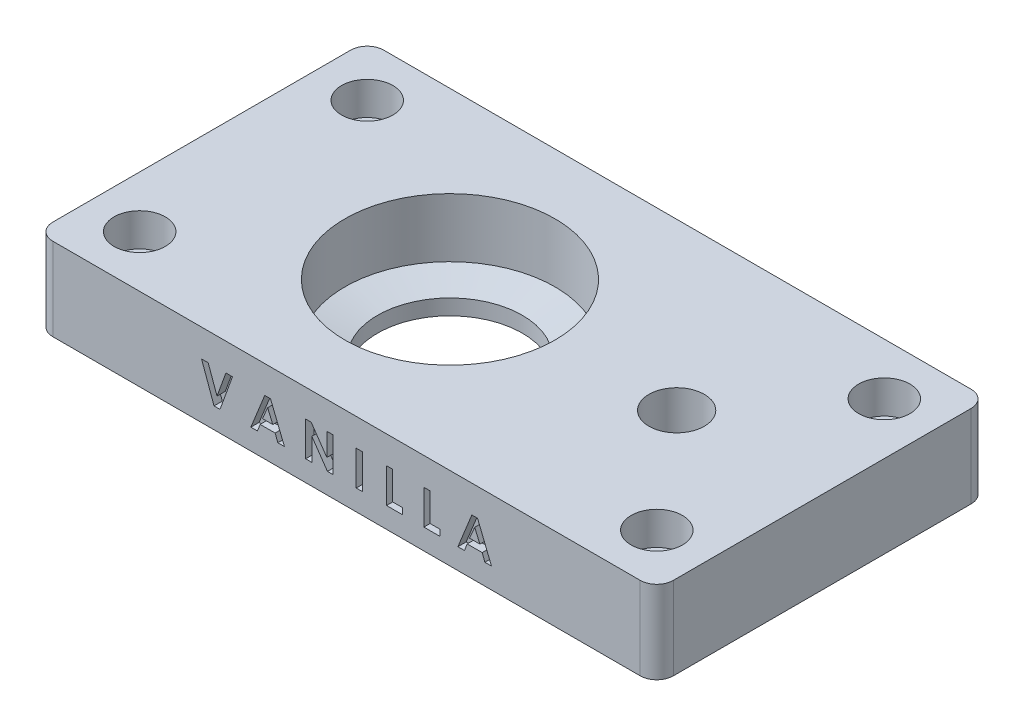
SolidWorks part; units mm, degrees
material "ABS"
ref_plane "Front Plane" through (0, 0, 0) normal (0, 0, 1) x (1, 0, 0)
ref_plane "Top Plane" through (0, 0, 0) normal (0, 1, 0) x (1, 0, 0)
ref_plane "Right Plane" through (0, 0, 0) normal (1, 0, 0) x (0, 0, -1)
sketch "Sketch1" plane through (0, 0, 0) normal (0, 1, 0) x (1, 0, 0)
  line L0 (0, 0) -> (34.798, 0) construction
  line L1 (-38.1, -25.4) -> (57.15, -25.4)
  line L2 (-38.1, -25.4) -> (-38.1, 25.4)
  line L3 (-38.1, 25.4) -> (57.15, 25.4)
  line L4 (57.15, -25.4) -> (57.15, 25.4)
  point P0 (0, 0)
  dimension "D1" = 95.25
  dimension "D2" = 50.8
  dimension "D3" = 34.798
extrude "Boss-Extrude1" add sketch "Sketch1" along normal blind 12.7
sketch "Sketch4" plane through (0, 12.7, 0) normal (0, 1, 0) x (1, 0, 0)
  line L5 (57.15, -25.4) -> (57.15, 25.4) construction
  line L6 (-38.1, -25.4) -> (57.15, -25.4) construction
  line L7 (57.15, 25.4) -> (-38.1, 25.4) construction
  line L8 (-38.1, 25.4) -> (-38.1, -25.4) construction
  circle A0 centre (-30.1625, 17.4625) radius 2.54
  circle A1 centre (49.2125, 17.4625) radius 2.54
  circle A2 centre (49.2125, -17.4625) radius 2.54
  circle A3 centre (-30.1625, -17.4625) radius 2.54
  point P0 (0, 0)
  dimension "D3" = 5.08
  dimension "D4" = 5.08
  dimension "D5" = 5.08
  dimension "D6" = 5.08
  dimension "D1" = 7.9375
  dimension "D2" = 7.9375
  dimension "D9" = 7.9375
  dimension "D7" = 7.9375
  dimension "D8" = 7.9375
  dimension "D10" = 7.9375
  dimension "D11" = 7.9375
  dimension "D12" = 7.9375
extrude "Cut-Extrude3" cut sketch "Sketch4" against normal through all
fillet "Fillet2" radius 2.54 4 edges at (-38.1, 6.35, 25.4) (57.15, 6.35, 25.4) (57.15, 6.35, -25.4) (-38.1, 6.35, -25.4)
sketch "Sketch6" plane through (0, 0, 0) normal (0, 0, 1) x (1, 0, 0)
  line L0 (0, 0) -> (0, 12.7)
  line L1 (-35.56, 12.7) -> (54.61, 12.7) construction
  line L2 (0, 12.7) -> (-16.129, 12.7)
  line L3 (-16.129, 12.7) -> (-16.129, 3.6513)
  line L5 (-35.56, 0) -> (54.61, 0) construction
  line L6 (-11.1125, 0) -> (0, 0)
  line L7 (-11.1125, 0) -> (-11.1125, 2.3813)
  line L8 (-11.1125, 2.3813) -> (-16.129, 3.6513)
  line L9 (-38.1, 0) -> (-38.1, 12.7) construction
  dimension "D1" = 16.129
  dimension "D2" = 11.1125
  dimension "D3" = 1.27
  dimension "D4" = 2.3813
  dimension "D5" = 38.1
revolve "Cut-Revolve1" cut sketch "Sketch6" angle 360 about L0
sketch "Sketch8" plane through (0, 12.7, 0) normal (0, 1, 0) x (1, 0, 0)
  line L0 (57.15, -22.86) -> (57.15, 22.86) construction
  circle A1 centre (34.798, 0) radius 4.25
  circle A2 centre (0, 0) radius 11.1125 construction
  point P5 (57.15, 0)
  dimension "D1" = 34.798
  dimension "D2" = 8.5
extrude "Cut-Extrude4" cut sketch "Sketch8" against normal blind 6.35
sketch "Sketch9" plane through (0, 0, 25.4) normal (0, 0, 1) x (1, 0, 0)
  line L0 (-35.56, 3.175) -> (54.61, 3.175) construction
  line L1 (-35.56, 12.7) -> (-35.56, 0) construction
  line L2 (54.61, 0) -> (54.61, 12.7) construction
  text T0 "<b>VANILLA</b>" font "Century Gothic" height in points 20
  point P6 (-35.56, 6.35)
  dimension "D1" = 3.175
extrude "Cut-Extrude5" cut sketch "Sketch9" against normal blind 1.27
sketch "Sketch10" plane through (0, 12.7, 0) normal (0, 1, 0) x (1, 0, 0)
  circle A0 centre (-30.1625, 17.4625) radius 3.937
  circle A1 centre (-30.1625, -17.4625) radius 3.937
  circle A2 centre (49.2125, 17.4625) radius 3.937
  circle A3 centre (49.2125, -17.4625) radius 3.937
  dimension "D1" = 7.874
  dimension "D2" = 7.874
  dimension "D3" = 7.874
  dimension "D4" = 7.874
extrude "Cut-Extrude6" cut sketch "Sketch10" against normal blind 5.08
